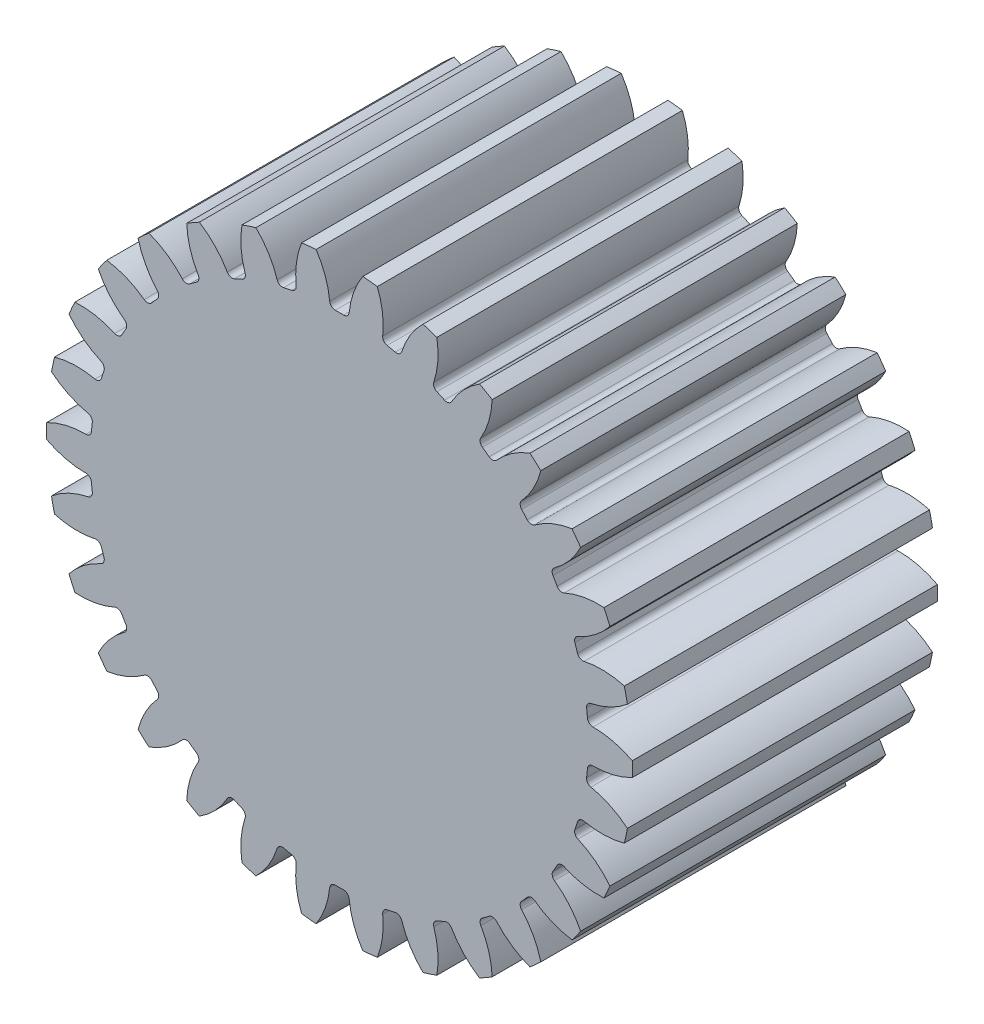
SolidWorks part; units mm, degrees
ref_plane "Front Plane" through (0, 0, 0) normal (0, 0, 1) x (1, 0, 0)
ref_plane "Top Plane" through (0, 0, 0) normal (0, 1, 0) x (1, 0, 0)
ref_plane "Right Plane" through (0, 0, 0) normal (1, 0, 0) x (0, 0, -1)
sketch "Sketch1" plane through (0, 0, 0) normal (0, 0, 1) x (1, 0, 0)
  circle A0 centre (0, 0) radius 18
  circle A1 centre (0, 0) radius 19.2
  circle A2 centre (0, 0) radius 16.32
  dimension "D1" = 36
  dimension "D2" = 38.4
  dimension "D3" = 2.88
extrude "Boss-Extrude1" add sketch "Sketch1" along normal mid plane 20 contours A1
sketch "Sketch2" plane through (0, 0, 0) normal (0, 0, 1) x (1, 0, 0)
  line L0 (0, 0) -> (0, 19.2) construction
  line L1 (-0.942, 17.9753) -> (0.942, 17.9753) construction
  line L2 (0, 0) -> (-0.6156, 16.3084) construction
  line L3 (0, 15.3871) -> (-1.7249, 20.1262) construction
  line L4 (0, 0) -> (2.0069, 19.0948) construction
  line L5 (0.942, 17.9753) -> (2.8158, 17.7784) construction
  circle A0 centre (0, 0) radius 19.2 construction
  arc A1 (-2.3105, 20.0674) -> (-0.6156, 16.3084) centre (-6.0896, 16.1018) cw
  arc A2 (2.3105, 20.0674) -> (0.6156, 16.3084) centre (6.0896, 16.1018) ccw
  circle A3 centre (0, 0) radius 16.32 construction
  arc A4 (0.6156, 16.3084) -> (-0.6156, 16.3084) centre (0, 0) ccw
  circle A6 centre (0, 0) radius 18 construction
  circle A7 centre (0, 0) radius 20.2
  arc A8 (2.3105, 20.0674) -> (-2.3105, 20.0674) centre (0, 0) ccw
  circle A9 centre (0, 0) radius 19.2 construction
  dimension "D2" = 20
  dimension "D3" = 6
  dimension "D1" = 1
extrude "Cut-Extrude1" cut sketch "Sketch2" against normal through all both and the other way through all
fillet "Fillet1" radius 0.36 2 edges at (0.6156, 16.3084, 0) (-0.6156, 16.3084, 0)
pattern_circular "CirPattern1" count 30 over 360 about axis through (0, 0, 0) along (0, 0, 1) of "Fillet1", "Cut-Extrude1"
equation "\"module\"= 1.2"
equation "\"num of teeth\" = 30"
equation "\"pressure angle\"= 20"
equation "\"helix angle\"= 30"
equation "\"pitch circle dia\"= \"module\" * \"num of teeth\""
equation "\"tip dia\"= \"pitch circle dia\" + ( 2 + \"module\" )"
equation "\"root dia\"= \"pitch circle dia\" - ( 2.5 * \"module\" )"
equation "\"addendum length\"= 1 * \"module\""
equation "\"D1@Sketch1\"=\"pitch circle dia\""
equation "\"out dia\"= ( \"num of teeth\" + 2 ) * \"module\""
equation "\"D2@Sketch1\"=\"out dia\""
equation "\"btwn root dia\"= \"module\" * IIF ( \"module\" = > 1.25 , 2.25 , 2.4 )"
equation "\"D3@Sketch1\"=\"btwn root dia\""
equation "\"deg teeth\"= 180 / \"num of teeth\""
equation "\"D3@Sketch2\"=\"deg teeth\""
equation "\"D1@Fillet1\"=.3 * \"module\""
equation "\"D1@CirPattern1\"=\"num of teeth\""
